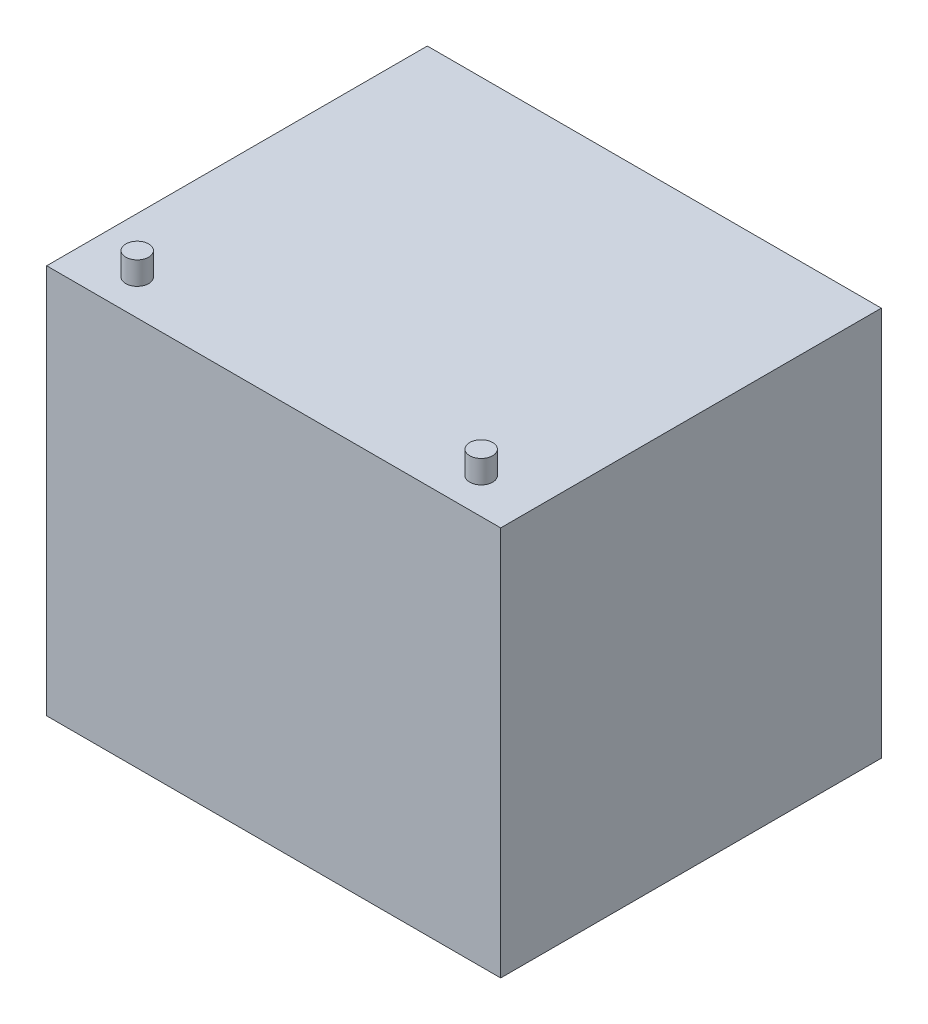
SolidWorks part; units mm, degrees
material "Custom Plastic"
ref_plane "Front Plane" through (0, 0, 0) normal (0, 0, 1) x (1, 0, 0)
ref_plane "Top Plane" through (0, 0, 0) normal (0, 1, 0) x (1, 0, 0)
ref_plane "Right Plane" through (0, 0, 0) normal (1, 0, 0) x (0, 0, -1)
sketch "Sketch1" plane through (0, 0, 0) normal (0, 1, 0) x (1, 0, 0)
  line L1 (-99, 83) -> (99, 83)
  line L2 (-99, 83) -> (-99, -83)
  line L3 (-99, -83) -> (99, -83)
  line L4 (99, 83) -> (99, -83)
  line L5 (-99, 83) -> (99, -83) construction
  line L6 (-99, -83) -> (99, 83) construction
  point P0 (0, 0)
  dimension "D1" = 166
  dimension "D2" = 198
extrude "Boss-Extrude1" add sketch "Sketch1" along normal blind 170
sketch "Sketch2" plane through (0, 170, 0) normal (0, 1, 0) x (1, 0, 0)
  circle A0 centre (-75, -67.5) radius 5
  circle A1 centre (75, -67.5) radius 5
extrude "Boss-Extrude2" add sketch "Sketch2" along normal blind 10
